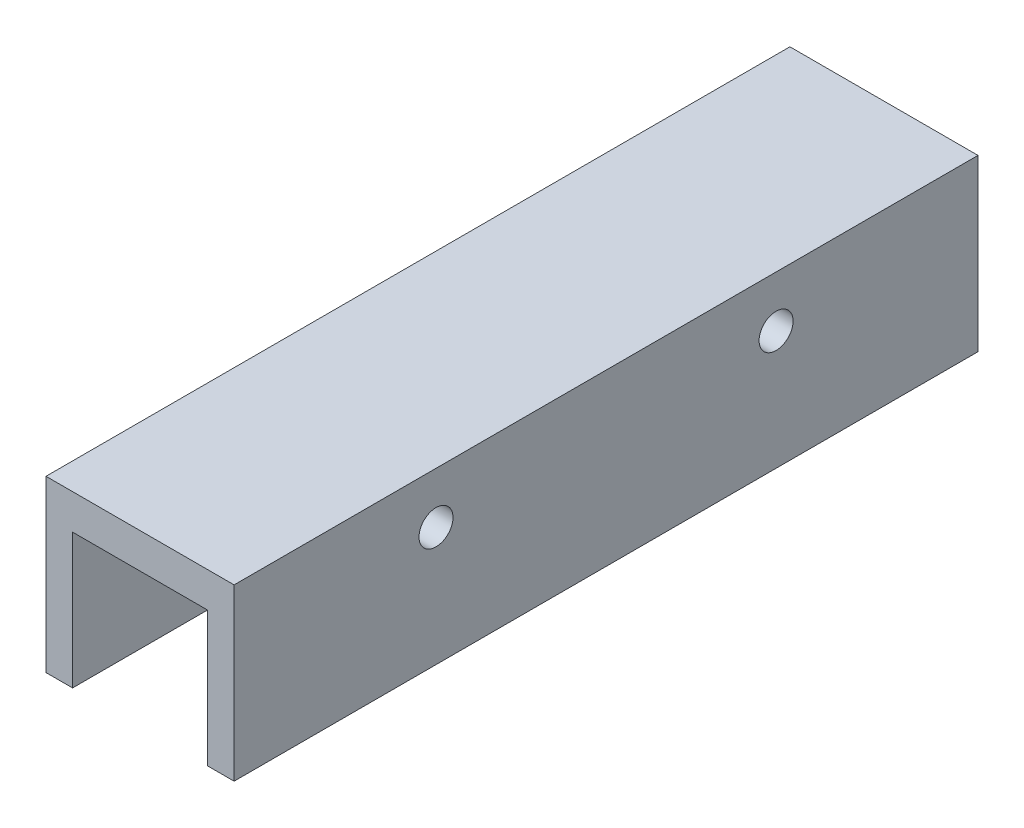
SolidWorks part; units mm, degrees
ref_plane "Front Plane" through (0, 0, 0) normal (0, 0, 1) x (1, 0, 0)
ref_plane "Top Plane" through (0, 0, 0) normal (0, 1, 0) x (1, 0, 0)
ref_plane "Right Plane" through (0, 0, 0) normal (1, 0, 0) x (0, 0, -1)
sketch "Sketch2" plane through (0, 0, 0) normal (0, 0, 1) x (1, 0, 0)
  line L0 (319.8414, 0) -> (-319.8414, 0) construction
  line L2 (0, 0) -> (0, 20.32)
  line L3 (0, 20.32) -> (22.479, 20.32)
  line L4 (22.479, 0) -> (22.479, 20.32)
  line L44 (19.304, 16.129) -> (19.304, 0)
  line L47 (3.175, 0) -> (3.175, 16.129)
  line L48 (3.175, 16.129) -> (19.304, 16.129)
  line L49 (0, 0) -> (3.175, 0)
  line L50 (19.304, 0) -> (22.479, 0)
  dimension "D1" = 20.32
  dimension "D2" = 22.479
  dimension "D3" = 3.175
  dimension "D4" = 16.129
  dimension "D5" = 3.175
  dimension "D7" = 16.129
extrude "Boss-Extrude2" add sketch "Sketch2" against normal blind 88.9
sketch "Sketch19" plane through (0, 0, 0) normal (1, 0, 0) x (0, 0, -1)
  line L0 (0, 265.0009) -> (0, -265.0009) construction
  line L1 (319.8414, 0) -> (-319.8414, 0) construction
  line L2 (88.9, 0) -> (88.9, 20.32) construction
  circle A0 centre (24.13, 14.224) radius 2.032
  circle A1 centre (64.77, 14.224) radius 2.032
  dimension "D2" = 4.064
  dimension "D5" = 4.064
  dimension "D1" = 24.13
  dimension "D3" = 14.224
  dimension "D4" = 40.64
  dimension "D6" = 14.224
  dimension "D7" = 24.13
extrude "Cut-Extrude3" cut sketch "Sketch19" along normal through all
sketch "Sketch20" plane through (22.479, 0, 0) normal (1, 0, 0) x (0, 0, -1)
